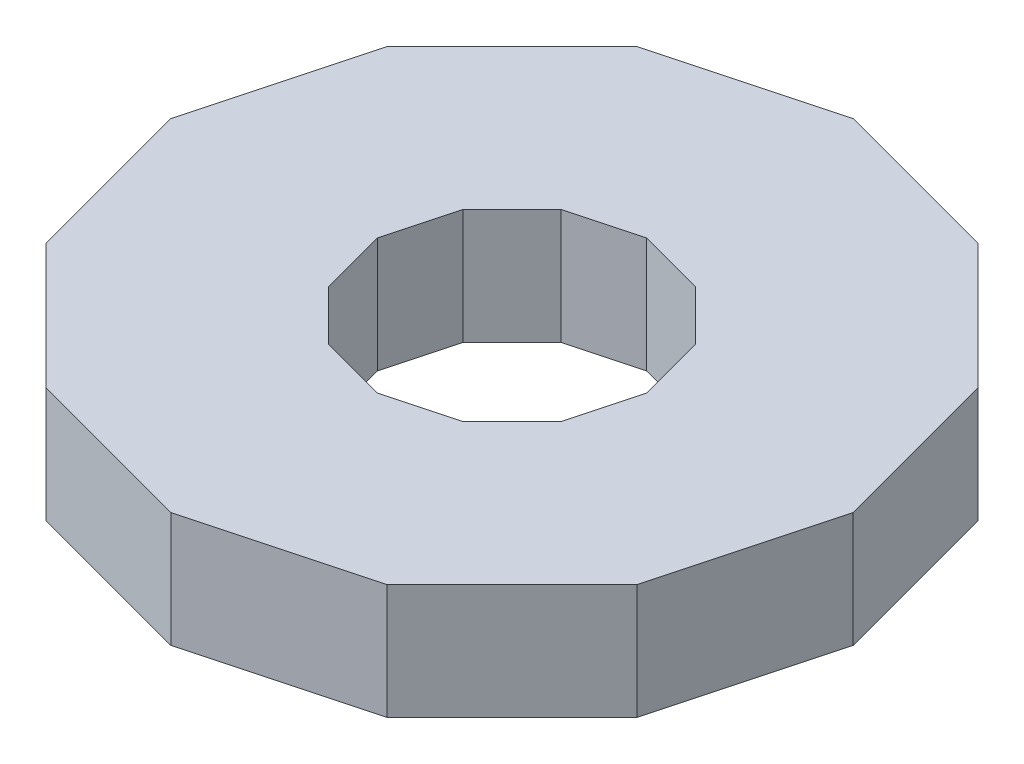
SolidWorks part; units mm, degrees
ref_plane "Front Plane" through (0, 0, 0) normal (0, 0, 1) x (1, 0, 0)
ref_plane "Top Plane" through (0, 0, 0) normal (0, 1, 0) x (1, 0, 0)
ref_plane "Right Plane" through (0, 0, 0) normal (1, 0, 0) x (0, 0, -1)
sketch "Sketch1" plane through (0, 0, 0) normal (0, 1, 0) x (1, 0, 0)
  line L0 (0, 0) -> (22.2446, 0) construction
  line L1 (56.4294, 0) -> (48.8693, 28.2147)
  line L2 (48.8693, 28.2147) -> (28.2147, 48.8693)
  line L3 (28.2147, 48.8693) -> (0, 56.4294)
  line L4 (0, 56.4294) -> (-28.2147, 48.8693)
  line L5 (-28.2147, 48.8693) -> (-48.8693, 28.2147)
  line L6 (-48.8693, 28.2147) -> (-56.4294, 0)
  line L7 (-56.4294, 0) -> (-48.8693, -28.2147)
  line L8 (-48.8693, -28.2147) -> (-28.2147, -48.8693)
  line L9 (-28.2147, -48.8693) -> (0, -56.4294)
  line L10 (0, -56.4294) -> (28.2147, -48.8693)
  line L11 (28.2147, -48.8693) -> (48.8693, -28.2147)
  line L12 (48.8693, -28.2147) -> (56.4294, 0)
  line L13 (22.2446, 0) -> (19.2644, 11.1223)
  line L14 (19.2644, 11.1223) -> (11.1223, 19.2644)
  line L15 (11.1223, 19.2644) -> (0, 22.2446)
  line L16 (0, 22.2446) -> (-11.1223, 19.2644)
  line L17 (-11.1223, 19.2644) -> (-19.2644, 11.1223)
  line L18 (-19.2644, 11.1223) -> (-22.2446, 0)
  line L19 (-22.2446, 0) -> (-19.2644, -11.1223)
  line L20 (-19.2644, -11.1223) -> (-11.1223, -19.2644)
  line L21 (-11.1223, -19.2644) -> (0, -22.2446)
  line L22 (0, -22.2446) -> (11.1223, -19.2644)
  line L23 (11.1223, -19.2644) -> (19.2644, -11.1223)
  line L24 (19.2644, -11.1223) -> (22.2446, 0)
  circle A0 centre (0, 0) radius 54.5066 construction
  circle A1 centre (0, 0) radius 21.4866 construction
  dimension "D1" = 33.02
  dimension "D2" = 29.21
  dimension "D3" = 54.5066
extrude "Boss-Extrude1" add sketch "Sketch1" along normal blind 19.05
